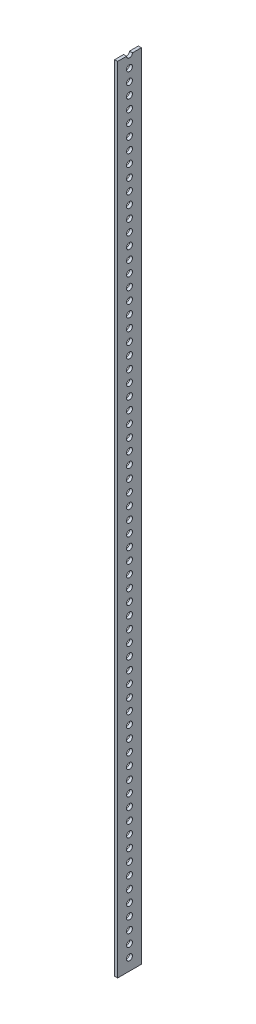
SolidWorks part; units mm, degrees
ref_plane "Front Plane" through (0, 0, 0) normal (0, 0, 1) x (1, 0, 0)
ref_plane "Top Plane" through (0, 0, 0) normal (0, 1, 0) x (1, 0, 0)
ref_plane "Right Plane" through (0, 0, 0) normal (1, 0, 0) x (0, 0, -1)
sketch "Sketch1" plane through (0, 0, 0) normal (1, 0, 0) x (0, 0, -1)
  line L1 (-12.7, -698.5) -> (12.7, -698.5)
  line L2 (-12.7, -698.5) -> (-12.7, 698.5)
  line L3 (-12.7, 698.5) -> (12.7, 698.5)
  line L4 (12.7, -698.5) -> (12.7, 698.5)
  line L5 (-12.7, -698.5) -> (12.7, 698.5) construction
  line L6 (-12.7, 698.5) -> (12.7, -698.5) construction
  circle A0 centre (0, -685.8) radius 3.175
  circle A1 centre (0, -673.1) radius 3.175
  circle A2 centre (0, -660.4) radius 3.175
  circle A3 centre (0, -647.7) radius 3.175
  circle A4 centre (0, -635) radius 3.175
  circle A5 centre (0, -622.3) radius 3.175
  circle A6 centre (0, -609.6) radius 3.175
  circle A7 centre (0, -596.9) radius 3.175
  circle A8 centre (0, -584.2) radius 3.175
  circle A9 centre (0, -571.5) radius 3.175
  circle A10 centre (0, -558.8) radius 3.175
  circle A11 centre (0, -546.1) radius 3.175
  circle A12 centre (0, -533.4) radius 3.175
  circle A13 centre (0, -520.7) radius 3.175
  circle A14 centre (0, -508) radius 3.175
  circle A15 centre (0, -495.3) radius 3.175
  circle A16 centre (0, -482.6) radius 3.175
  circle A17 centre (0, -469.9) radius 3.175
  circle A18 centre (0, -457.2) radius 3.175
  circle A19 centre (0, -444.5) radius 3.175
  circle A20 centre (0, -431.8) radius 3.175
  circle A21 centre (0, -419.1) radius 3.175
  circle A22 centre (0, -406.4) radius 3.175
  circle A23 centre (0, -393.7) radius 3.175
  circle A24 centre (0, -381) radius 3.175
  circle A25 centre (0, -368.3) radius 3.175
  circle A26 centre (0, -355.6) radius 3.175
  circle A27 centre (0, -342.9) radius 3.175
  circle A28 centre (0, -330.2) radius 3.175
  circle A29 centre (0, -317.5) radius 3.175
  circle A30 centre (0, -304.8) radius 3.175
  circle A31 centre (0, -292.1) radius 3.175
  circle A32 centre (0, -279.4) radius 3.175
  circle A33 centre (0, -266.7) radius 3.175
  circle A34 centre (0, -254) radius 3.175
  circle A35 centre (0, -241.3) radius 3.175
  circle A36 centre (0, -228.6) radius 3.175
  circle A37 centre (0, -215.9) radius 3.175
  circle A38 centre (0, -203.2) radius 3.175
  circle A39 centre (0, -190.5) radius 3.175
  circle A40 centre (0, -177.8) radius 3.175
  circle A41 centre (0, -165.1) radius 3.175
  circle A42 centre (0, -152.4) radius 3.175
  circle A43 centre (0, -139.7) radius 3.175
  circle A44 centre (0, -127) radius 3.175
  circle A45 centre (0, -114.3) radius 3.175
  circle A46 centre (0, -101.6) radius 3.175
  circle A47 centre (0, -88.9) radius 3.175
  circle A48 centre (0, -76.2) radius 3.175
  circle A49 centre (0, -63.5) radius 3.175
  circle A50 centre (0, -50.8) radius 3.175
  circle A51 centre (0, -38.1) radius 3.175
  circle A52 centre (0, -25.4) radius 3.175
  circle A53 centre (0, -12.7) radius 3.175
  circle A54 centre (0, 0) radius 3.175
  circle A55 centre (0, 12.7) radius 3.175
  circle A56 centre (0, 25.4) radius 3.175
  circle A57 centre (0, 38.1) radius 3.175
  circle A58 centre (0, 50.8) radius 3.175
  circle A59 centre (0, 63.5) radius 3.175
  circle A60 centre (0, 76.2) radius 3.175
  circle A61 centre (0, 88.9) radius 3.175
  circle A62 centre (0, 101.6) radius 3.175
  circle A63 centre (0, 114.3) radius 3.175
  circle A64 centre (0, 127) radius 3.175
  circle A65 centre (0, 139.7) radius 3.175
  circle A66 centre (0, 152.4) radius 3.175
  circle A67 centre (0, 165.1) radius 3.175
  circle A68 centre (0, 177.8) radius 3.175
  circle A69 centre (0, 190.5) radius 3.175
  circle A70 centre (0, 203.2) radius 3.175
  circle A71 centre (0, 215.9) radius 3.175
  circle A72 centre (0, 228.6) radius 3.175
  circle A73 centre (0, 241.3) radius 3.175
  circle A74 centre (0, 254) radius 3.175
  circle A75 centre (0, 266.7) radius 3.175
  circle A76 centre (0, 279.4) radius 3.175
  circle A77 centre (0, 292.1) radius 3.175
  circle A78 centre (0, 304.8) radius 3.175
  circle A79 centre (0, 317.5) radius 3.175
  circle A80 centre (0, 330.2) radius 3.175
  circle A81 centre (0, 342.9) radius 3.175
  circle A82 centre (0, 355.6) radius 3.175
  circle A83 centre (0, 368.3) radius 3.175
  circle A84 centre (0, 381) radius 3.175
  circle A85 centre (0, 393.7) radius 3.175
  circle A86 centre (0, 406.4) radius 3.175
  circle A87 centre (0, 419.1) radius 3.175
  circle A88 centre (0, 431.8) radius 3.175
  circle A89 centre (0, 444.5) radius 3.175
  circle A90 centre (0, 457.2) radius 3.175
  circle A91 centre (0, 469.9) radius 3.175
  circle A92 centre (0, 482.6) radius 3.175
  circle A93 centre (0, 495.3) radius 3.175
  circle A94 centre (0, 508) radius 3.175
  circle A95 centre (0, 520.7) radius 3.175
  circle A96 centre (0, 533.4) radius 3.175
  circle A97 centre (0, 546.1) radius 3.175
  circle A98 centre (0, 558.8) radius 3.175
  circle A99 centre (0, 571.5) radius 3.175
  circle A100 centre (0, 584.2) radius 3.175
  circle A101 centre (0, 596.9) radius 3.175
  circle A102 centre (0, 609.6) radius 3.175
  circle A103 centre (0, 622.3) radius 3.175
  circle A104 centre (0, 635) radius 3.175
  circle A105 centre (0, 647.7) radius 3.175
  circle A106 centre (0, 660.4) radius 3.175
  circle A107 centre (0, 673.1) radius 3.175
  circle A108 centre (0, 685.8) radius 3.175
  point P0 (0, 0)
  dimension "D1" = 109
extrude "Boss-Extrude1" add sketch "Sketch1" along normal blind 3.175
sketch "Sketch2" plane through (0, 0, 0) normal (-1, 0, 0) x (0, 0, 1)
  line L0 (12.7, 698.5) -> (12.7, -698.5) construction
  line L1 (-12.7, 698.5) -> (12.7, 698.5)
  line L2 (-12.7, 698.5) -> (-12.7, 152.2891)
  line L3 (-12.7, 152.2891) -> (12.7, 152.2891)
  line L4 (12.7, 698.5) -> (12.7, 152.2891)
extrude "Cut-Extrude1" cut sketch "Sketch2" against normal through all
